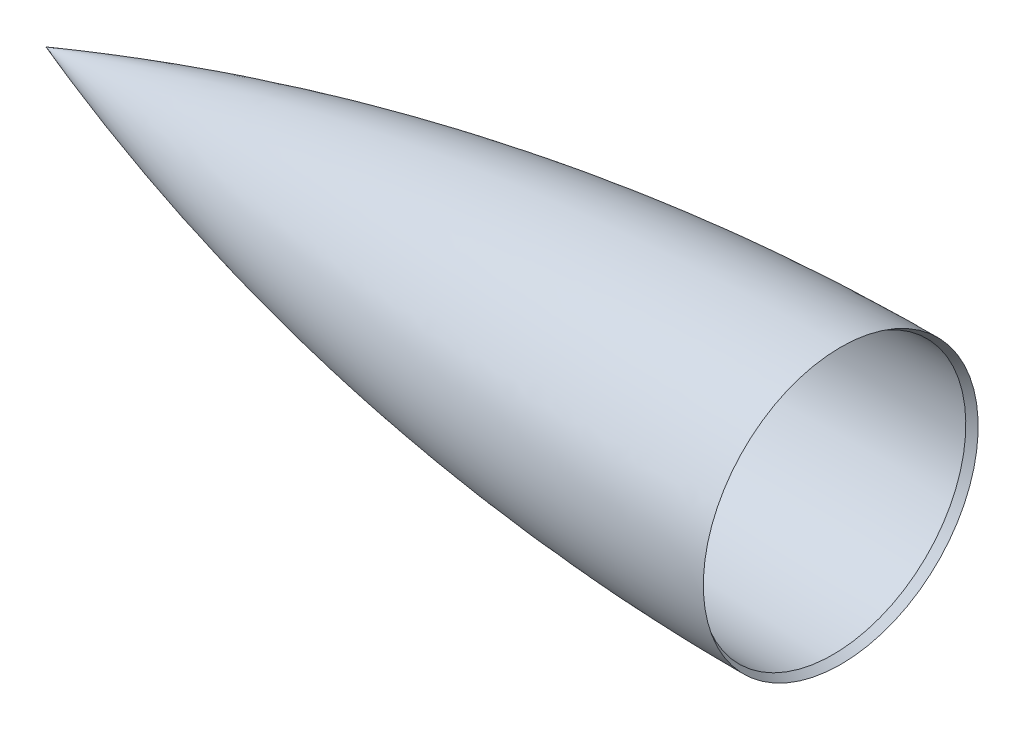
SolidWorks part; units mm, degrees
ref_plane "Front Plane" through (0, 0, 0) normal (0, 0, 1) x (1, 0, 0)
ref_plane "Top Plane" through (0, 0, 0) normal (0, 1, 0) x (1, 0, 0)
ref_plane "Right Plane" through (0, 0, 0) normal (1, 0, 0) x (0, 0, -1)
sketch "Sketch1" plane through (0, 0, 0) normal (0, 0, 1) x (1, 0, 0)
  line L0 (0, 0) -> (-229, 0) construction
  line L1 (0, 36.6) -> (0, -642.3338) construction
  line L3 (-229, 0) -> (-219.9054, 0)
  line L4 (83, 38.1) -> (2.5981, 38.1)
  line L7 (0, 39.6) -> (83, 39.6)
  line L8 (83, 38.1) -> (83, 39.6)
  line L9 (0, 36.6) -> (2.5981, 38.1)
  line L10 (0, 36.6) -> (119.7357, 36.6) construction
  line L11 (2.5981, 38.1) -> (119.7357, 38.1) construction
  line L12 (119.7357, 36.6) -> (119.7357, 38.1) construction
  line L13 (-79.2, 81.783) -> (-79.2, 33.6764) construction
  line L15 (0, 39.6) -> (-2.2582, 38.2963)
  line L16 (-79.2, 33.6764) -> (-82.9448, 31.5143)
  line L17 (-79.2, 31.9647) -> (-79.2, -62.4632) construction
  circle A0 centre (0, -642.3338) radius 681.9338 construction
  arc A1 (-229, 0) -> (0, 39.6) centre (0, -642.3338) cw
  arc A2 (-219.9054, 0) -> (0, 36.6) centre (0, -642.3338) cw
  arc A3 (-227.9926, -2.8258) -> (0, 36.6) centre (0, -642.3338) cw construction
  arc A4 (-79.2, 33.6764) -> (-2.2582, 38.2963) centre (0, -642.3338) cw
  arc A5 (-220.4561, 1.6084) -> (0, 38.3) centre (0, -642.3338) cw construction
  point P0 (0, 39.6)
  dimension "D1" = 39.6
  dimension "D2" = 229
  dimension "D3" = 681.9338
  dimension "D5" = 83
  dimension "D6" = 1.5
  dimension "D7" = 30
  dimension "D8" = 80.4019
  dimension "D9" = 1.5
  dimension "D10" = 38.1
  dimension "D11" = 1.7
  dimension "D12" = 79.2
  dimension "D13" = 30
  dimension "D14" = 30
  dimension "D4" = 3
revolve "Revolve1" add sketch "Sketch1" angle 360 about L0
